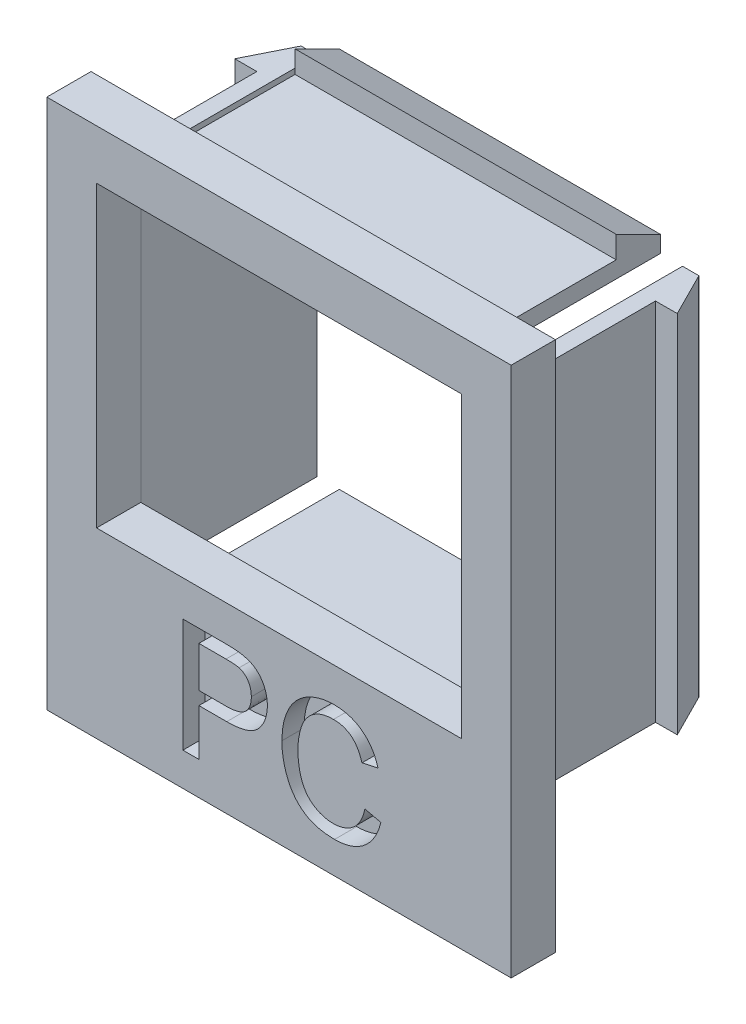
SolidWorks part; units mm, degrees
ref_plane "Спереди" through (0, 0, 0) normal (0, 0, 1) x (1, 0, 0)
ref_plane "Сверху" through (0, 0, 0) normal (0, 1, 0) x (1, 0, 0)
ref_plane "Справа" through (0, 0, 0) normal (1, 0, 0) x (0, 0, -1)
sketch "Эскиз1" plane through (0, 0, 0) normal (0, 0, 1) x (1, 0, 0)
  line L1 (-9, 9) -> (9, 9)
  line L2 (-9, 9) -> (-9, -9)
  line L3 (-9, -9) -> (9, -9)
  line L4 (9, 9) -> (9, -9)
  line L5 (-9, 9) -> (9, -9) construction
  line L6 (-9, -9) -> (9, 9) construction
  line L7 (-10.5, 10.5) -> (10.5, 10.5)
  line L8 (-10.5, 10.5) -> (-10.5, -10.5)
  line L9 (-10.5, -10.5) -> (10.5, -10.5)
  line L10 (10.5, 10.5) -> (10.5, -10.5)
  line L11 (-10.5, 10.5) -> (10.5, -10.5) construction
  line L12 (-10.5, -10.5) -> (10.5, 10.5) construction
  point P0 (0, 0)
  point P6 (0, 0)
  dimension "D1" = 18
  dimension "D2" = 18
  dimension "D3" = 21
  dimension "D4" = 21
extrude "Бобышка-Вытянуть1" add sketch "Эскиз1" along normal blind 2
sketch "Эскиз2" plane through (0, 0, 2) normal (0, 0, 1) x (1, 0, 0)
  line L1 (-9, 9) -> (9, 9)
  line L2 (-9, 9) -> (-9, -9)
  line L3 (-9, -9) -> (9, -9)
  line L4 (9, 9) -> (9, -9)
  line L5 (-9, 9) -> (9, -9) construction
  line L6 (-9, -9) -> (9, 9) construction
  line L7 (-8.25, 8.25) -> (8.25, 8.25)
  line L8 (-8.25, 8.25) -> (-8.25, -8.25)
  line L9 (-8.25, -8.25) -> (8.25, -8.25)
  line L10 (8.25, 8.25) -> (8.25, -8.25)
  line L11 (-8.25, 8.25) -> (8.25, -8.25) construction
  line L12 (-8.25, -8.25) -> (8.25, 8.25) construction
  point P0 (0, 0)
  point P7 (0, 0)
  dimension "D1" = 16.5
extrude "Бобышка-Вытянуть2" add sketch "Эскиз2" against normal blind 10
sketch "Эскиз4" plane through (0, 0, 2) normal (0, 0, 1) x (1, 0, 0)
  line L0 (8.25, -8.25) -> (8.25, 8.25) construction
  line L1 (-8.25, -8.25) -> (8.25, -8.25)
  line L2 (-8.25, -8.25) -> (-8.25, -5.25)
  line L3 (-8.25, -5.25) -> (8.25, -5.25)
  line L4 (8.25, -8.25) -> (8.25, -5.25)
  dimension "D1" = 3
extrude "Бобышка-Вытянуть3" add sketch "Эскиз4" against normal blind 2
sketch "Эскиз5" plane through (0, 0, 2) normal (0, 0, 1) x (1, 0, 0)
  line L1 (-10.5, -10.5) -> (10.5, -10.5)
  line L2 (-10.5, -10.5) -> (-10.5, -13.5)
  line L3 (-10.5, -13.5) -> (10.5, -13.5)
  line L4 (10.5, -10.5) -> (10.5, -13.5)
  dimension "D1" = 3
extrude "Бобышка-Вытянуть4" add sketch "Эскиз5" against normal blind 2
sketch "Эскиз6" plane through (0, 0, 2) normal (0, 0, 1) x (1, 0, 0)
  text T0 "PC" font "Arial" height in points 20
extrude "Вырез-Вытянуть1" cut sketch "Эскиз6" against normal blind 1
sketch "Эскиз7" plane through (0, 0, -8) normal (0, 0, -1) x (-1, 0, 0)
  line L0 (-9, 9) -> (9, 9) construction
  line L1 (-8.25, 9) -> (-7.25, 9)
  line L2 (-8.25, 9) -> (-8.25, -9)
  line L3 (-8.25, -9) -> (-7.25, -9)
  line L4 (-7.25, 9) -> (-7.25, -9)
  line L5 (9, -9) -> (-9, -9) construction
  line L6 (-9, 9) -> (9, 9) construction
  line L7 (8.2728, 9) -> (7.2728, 9)
  line L8 (8.2728, 9) -> (8.2728, -9)
  line L9 (8.2728, -9) -> (7.2728, -9)
  line L10 (7.2728, 9) -> (7.2728, -9)
  dimension "D1" = 1
  dimension "D2" = 1
extrude "Вырез-Вытянуть2" cut sketch "Эскиз7" against normal blind 8
sketch "Эскиз8" plane through (0, 0, -8) normal (0, 0, -1) x (-1, 0, 0)
  line L0 (9, 9) -> (9, -9) construction
  line L1 (-9, 9) -> (-8.25, 9)
  line L2 (-9, 9) -> (-9, 8.25)
  line L3 (-9, 8.25) -> (-8.25, 8.25)
  line L4 (-8.25, 9) -> (-8.25, 8.25)
  line L5 (8.2728, 9) -> (9, 9)
  line L6 (8.2728, 9) -> (8.2728, 8.25)
  line L7 (8.2728, 8.25) -> (9, 8.25)
  line L8 (9, 9) -> (9, 8.25)
  line L9 (-8.25, -9) -> (-8.25, -5.25) construction
  line L10 (8.2728, -9) -> (9, -9)
  line L11 (8.2728, -9) -> (8.2728, -8.25)
  line L12 (8.2728, -8.25) -> (9, -8.25)
  line L13 (9, -9) -> (9, -8.25)
  line L14 (-9, -9) -> (-8.25, -9)
  line L15 (-9, -9) -> (-9, -8.25)
  line L16 (-9, -8.25) -> (-8.25, -8.25)
  line L17 (-8.25, -9) -> (-8.25, -8.25)
extrude "Вырез-Вытянуть3" cut sketch "Эскиз8" against normal blind 8
sketch "Эскиз10" plane through (0, 8.25, 0) normal (0, 1, 0) x (1, 0, 0)
  line L0 (-9, 8) -> (-10, 6)
  line L1 (-10, 6) -> (-9, 6)
  line L2 (-9, 0) -> (-9, 8) construction
  line L3 (-9, 6) -> (-9, 8)
  line L4 (-0.0114, 8) -> (0, 0)
  line L5 (7.25, 8) -> (-7.2728, 8) construction
  line L6 (8.9828, 6.0256) -> (8.9771, 8.0256)
  line L7 (9.9828, 6.0285) -> (8.9828, 6.0256)
  line L8 (8.9771, 8.0256) -> (9.9828, 6.0285)
  dimension "D1" = 2
  dimension "D2" = 1
extrude "Бобышка-Вытянуть5" add sketch "Эскиз10" against normal up to surface (16.5 mm away) contours L8 L6 L7 | L3 L0 L1 up to face at (-8.6364, -8.25, -4)
sketch "Эскиз12" plane through (-7.2728, 0, 0) normal (-1, 0, 0) x (0, 0, 1)
  line L0 (-8, 9) -> (-6, 10)
  line L1 (-6, 10) -> (-6, 9)
  line L2 (0, 9) -> (-8, 9) construction
  line L3 (-6, 9) -> (-8, 9)
  line L4 (0, 0) -> (-8, 0)
  line L5 (-8, 8.25) -> (-8, -8.25) construction
  line L6 (-6, -9) -> (-8, -9)
  line L7 (-6, -10) -> (-6, -9)
  line L8 (-8, -9) -> (-6, -10)
  line M5 (0, 9) -> (-8, 9)
  dimension "D1" = 2
  dimension "D2" = 1
extrude "Бобышка-Вытянуть6" add sketch "Эскиз12" against normal up to surface (14.5228 mm away) contours L1 L0 M5 | L6 L8 L7 up to face at (7.25, -8.625, -4)
